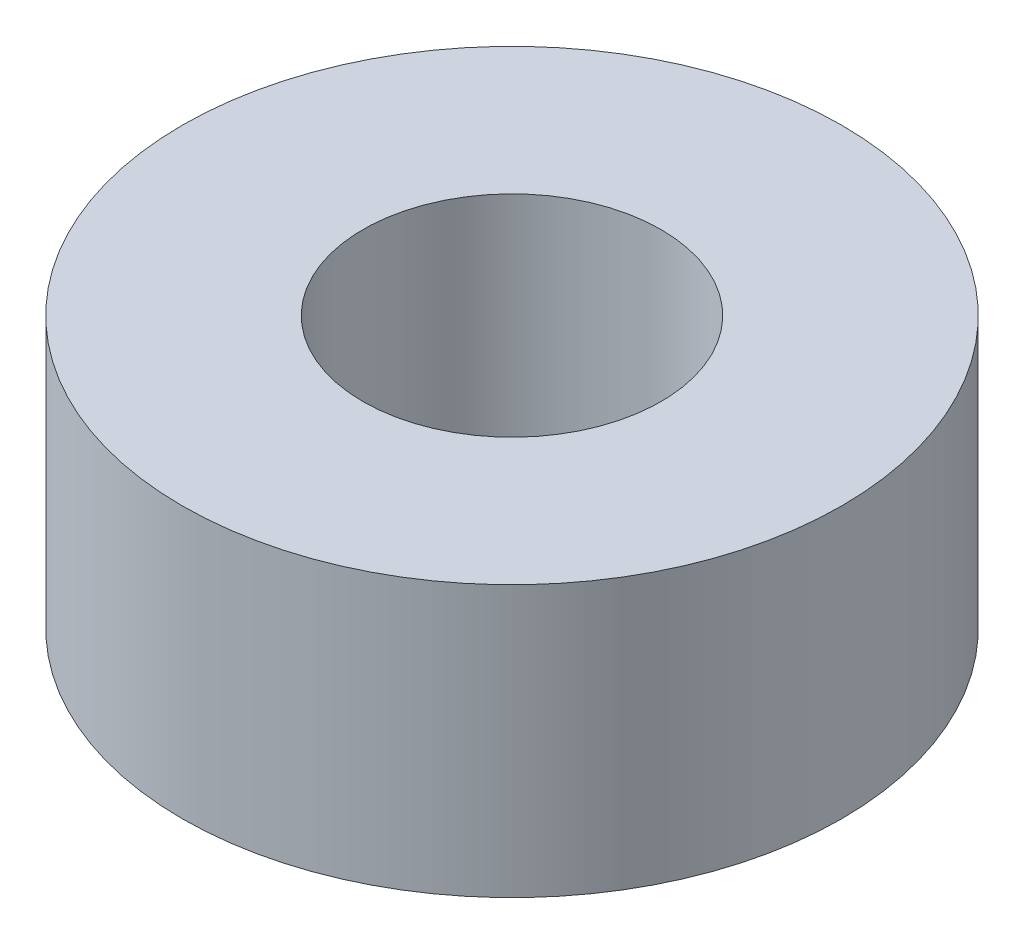
SolidWorks part; units mm, degrees
ref_plane "Front Plane" through (0, 0, 0) normal (0, 0, 1) x (1, 0, 0)
ref_plane "Top Plane" through (0, 0, 0) normal (0, 1, 0) x (1, 0, 0)
ref_plane "Right Plane" through (0, 0, 0) normal (1, 0, 0) x (0, 0, -1)
sketch "Sketch1" plane through (0, 0, 0) normal (0, 1, 0) x (1, 0, 0)
  circle A0 centre (0, 0) radius 1.65
  circle A1 centre (0, 0) radius 3.65
  dimension "D1" = 3.3
  dimension "D2" = 2
extrude "Boss-Extrude1" add sketch "Sketch1" along normal blind 3
